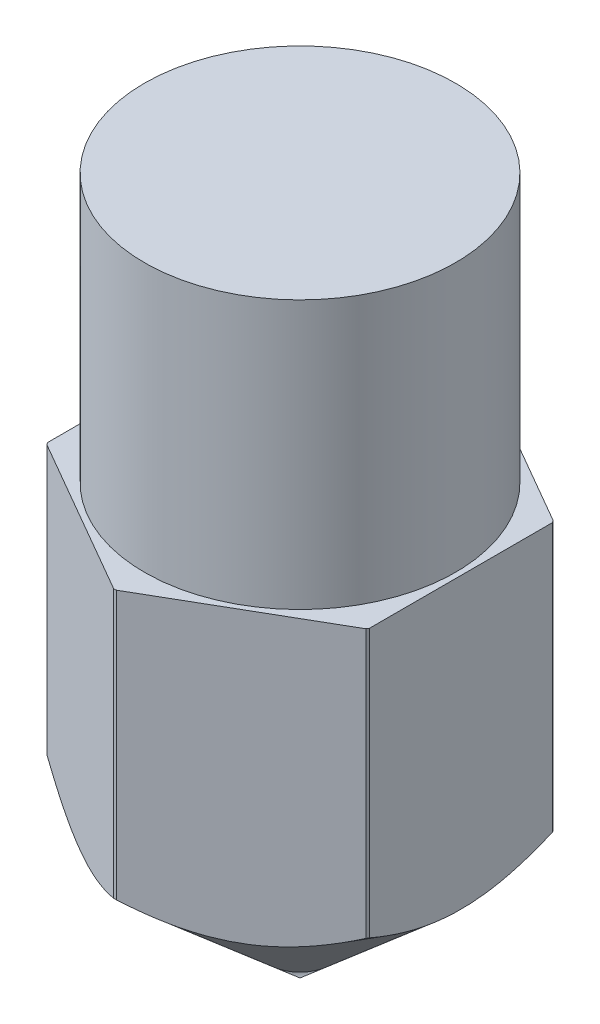
SolidWorks part; units mm, degrees
ref_plane "Ön Düzlem" through (0, 0, 0) normal (0, 0, 1) x (1, 0, 0)
ref_plane "Üst Düzlem" through (0, 0, 0) normal (0, 1, 0) x (1, 0, 0)
ref_plane "Sağ Düzlem" through (0, 0, 0) normal (1, 0, 0) x (0, 0, -1)
sketch "Sketch1" plane through (0, 0, 0) normal (0, 0, 1) x (1, 0, 0)
  line L0 (0, 0) -> (0, -13)
  line L1 (0, -13) -> (-3.45, -10)
  line L2 (-3.45, -10) -> (-3.45, -5)
  line L3 (-3.45, -5) -> (-2.9, -5)
  line L4 (-2.9, -5) -> (-2.9, 0)
  line L5 (-2.9, 0) -> (0, 0)
  dimension "D1" = 13
  dimension "D2" = 3.45
  dimension "D3" = 5
  dimension "D4" = 2.9
  dimension "D5" = 5
revolve "Revolve1" add sketch "Sketch1" angle 360 about L0
sketch "Sketch2" plane through (0, 0, 0) normal (0, 1, 0) x (1, 0, 0)
  line L1 (0, 3.4641) -> (-3, 1.7321)
  line L2 (-3, 1.7321) -> (-3, -1.7321)
  line L3 (-3, -1.7321) -> (0, -3.4641)
  line L4 (0, -3.4641) -> (3, -1.7321)
  line L5 (3, -1.7321) -> (3, 1.7321)
  line L6 (3, 1.7321) -> (0, 3.4641)
  circle A0 centre (0, 0) radius 3 construction
  dimension "D1" = 6
extrude "Cut-Extrude1" cut sketch "Sketch2" against normal blind 20 flip side to cut
